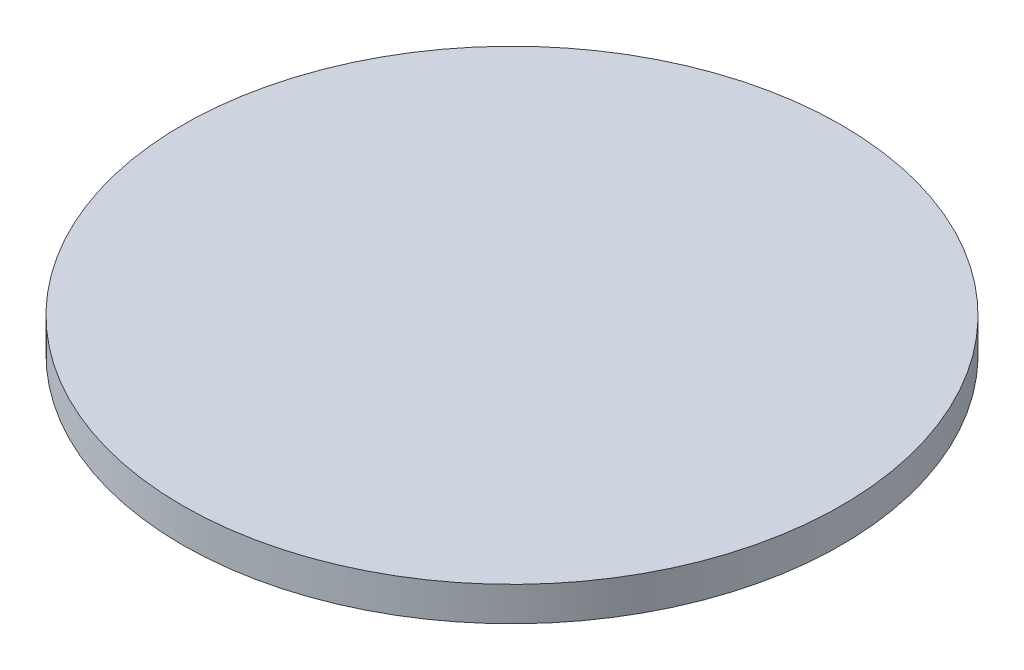
SolidWorks part; units mm, degrees
ref_plane "Front Plane" through (0, 0, 0) normal (0, 0, 1) x (1, 0, 0)
ref_plane "Top Plane" through (0, 0, 0) normal (0, 1, 0) x (1, 0, 0)
ref_plane "Right Plane" through (0, 0, 0) normal (1, 0, 0) x (0, 0, -1)
sketch "Sketch1" plane through (0, 0, 0) normal (0, 1, 0) x (1, 0, 0)
  circle A0 centre (0, 0) radius 22.21
  dimension "D1" = 44.42
extrude "Boss-Extrude1" add sketch "Sketch1" along normal blind 2.3
equation "\"can_diameter\"= 44.42"
equation "\"inlet_diameter\"=9.525"
equation "\"can_outer_diameter\"= 44.42"
equation "\"can_thickness\"= 2.3"
equation "\"can_height\"=104.902"
equation "\"D1@Sketch1\"=\"can_outer_diameter\""
equation "\"D1@Boss-Extrude1\"=\"can_thickness\""
